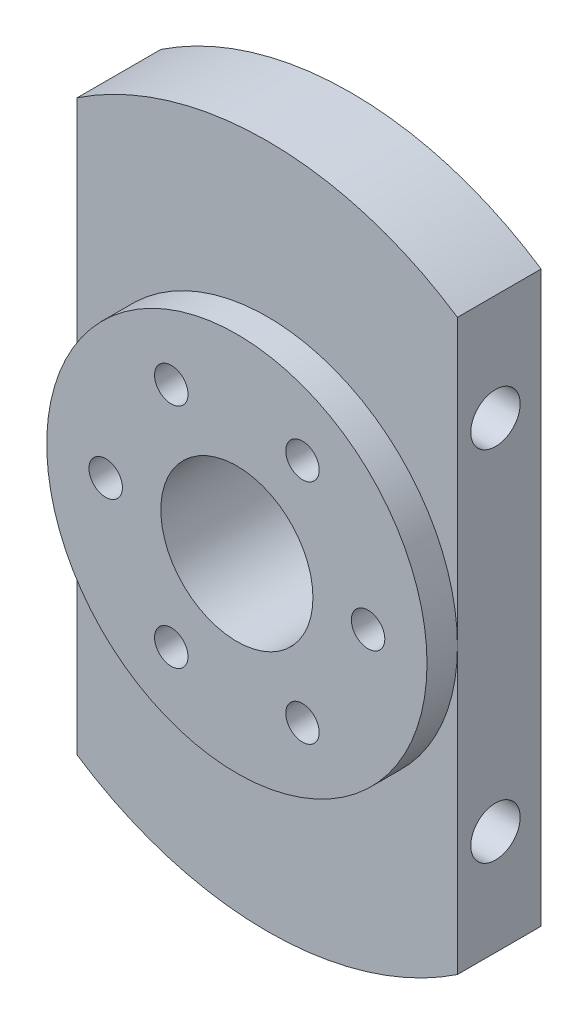
SolidWorks part; units mm, degrees
ref_plane "前视基准面" through (0, 0, 0) normal (0, 0, 1) x (1, 0, 0)
ref_plane "上视基准面" through (0, 0, 0) normal (0, 1, 0) x (1, 0, 0)
ref_plane "右视基准面" through (0, 0, 0) normal (1, 0, 0) x (0, 0, -1)
sketch "草图1" plane through (0, 0, 0) normal (0, 0, 1) x (1, 0, 0)
  circle A0 centre (0, 0) radius 45
  dimension "D1" = 90
extrude "凸台-拉伸1" add sketch "草图1" along normal blind 15
sketch "草图6" plane through (0, 0, 15) normal (0, 0, 1) x (1, 0, 0)
  circle A0 centre (0, 0) radius 10
extrude "切除-拉伸5" cut sketch "草图6" against normal blind 26
sketch "草图7" plane through (0, 0, 15) normal (0, 0, 1) x (1, 0, 0)
  circle A0 centre (17.25, 0) radius 2.2
  circle A1 centre (8.625, -14.9389) radius 2.2
  circle A2 centre (-8.625, -14.9389) radius 2.2
  circle A3 centre (-17.25, 0) radius 2.2
  circle A4 centre (-8.625, 14.9389) radius 2.2
  circle A5 centre (8.625, 14.9389) radius 2.2
  point P15 (0, 0)
  dimension "D1" = 4.4
  dimension "D2" = 17.25
  dimension "D3" = 6
extrude "切除-拉伸6" cut sketch "草图7" against normal through all
sketch "草图8" plane through (0, 0, 15) normal (0, 0, 1) x (1, 0, 0)
  line L0 (-45, 0) -> (45, 0) construction
  line L1 (-25, -37.4166) -> (-25, 37.4166)
  line L2 (0, 45) -> (0, -45) construction
  line L3 (25, -37.4166) -> (25, 37.4166)
  circle A0 centre (17.25, 0) radius 2.2 construction
  circle A1 centre (0, 0) radius 45
  circle A2 centre (0, 0) radius 45
  circle A3 centre (-17.25, 0) radius 2.2 construction
  circle A4 centre (17.25, 0) radius 2.2
  circle A5 centre (-17.25, 0) radius 2.2
  circle M11 centre (0, 0) radius 45
  dimension "D2" = 25
  dimension "D1" = 0
extrude "切除-拉伸7" cut sketch "草图8" against normal through all contours L1 M11 | L3 M11
sketch "草图9" plane through (25, 0, 0) normal (1, 0, 0) x (0, 0, -1)
  line L0 (-15, 0) -> (0, 0) construction
  line L5 (-15, 37.4166) -> (-15, -37.4166)
  line L6 (-15, -37.4166) -> (0, -37.4166)
  line L7 (0, -37.4166) -> (0, 37.4166)
  line L8 (0, 37.4166) -> (-15, 37.4166)
  line L9 (-15, 37.4166) -> (-15, -37.4166)
  line L10 (-15, -37.4166) -> (0, -37.4166)
  line L11 (0, -37.4166) -> (0, 37.4166)
  line L12 (0, 37.4166) -> (-15, 37.4166)
  circle A0 centre (-6, 23.45) radius 3.25
  circle A1 centre (-6, -23.63) radius 3.25
  dimension "D2" = 6.5
  dimension "D3" = 6.5
  dimension "D4" = 6
  dimension "D5" = 47.08
  dimension "D6" = 6
  dimension "D7" = 23.45
  dimension "D1" = 0
extrude "切除-拉伸8" cut sketch "草图9" against normal through all contours A0 | A1
sketch "草图11" plane through (0, 0, 0) normal (0, 0, -1) x (-1, 0, 0)
  circle A0 centre (-8.625, 14.9389) radius 4
  circle A1 centre (0, 0) radius 10
  circle A2 centre (0, 0) radius 10
  circle A3 centre (-8.625, -14.9389) radius 2.2
  circle A4 centre (-8.625, -14.9389) radius 2.2
  circle A5 centre (8.625, -14.9389) radius 2.2
  circle A6 centre (8.625, -14.9389) radius 2.2
  circle A7 centre (17.25, 0) radius 2.2
  circle A8 centre (17.25, 0) radius 2.2
  circle A9 centre (8.625, 14.9389) radius 2.2
  circle A10 centre (8.625, 14.9389) radius 2.2
  circle A11 centre (-8.625, 14.9389) radius 2.2
  circle A12 centre (-8.625, 14.9389) radius 2.2
  circle A13 centre (-17.25, 0) radius 2.2
  circle A14 centre (-17.25, 0) radius 2.2
  circle A15 centre (-17.25, 0) radius 4
  circle A16 centre (-8.625, -14.9389) radius 4
  circle A17 centre (8.625, 14.9389) radius 4
  circle A18 centre (8.625, -14.9389) radius 4
  circle A19 centre (17.25, 0) radius 4
  dimension "D8" = 8
  dimension "D9" = 8
  dimension "D10" = 8
  dimension "D11" = 8
  dimension "D12" = 8
  dimension "D13" = 8
  dimension "D1" = 0
  dimension "D2" = 0
  dimension "D3" = 0
  dimension "D4" = 0
  dimension "D5" = 0
  dimension "D6" = 0
  dimension "D7" = 0
extrude "切除-拉伸9" cut sketch "草图11" against normal blind 9 contours A15 | A0 | A16 | A18 | A19 | A17
sketch "草图12" plane through (25, 0, 0) normal (1, 0, 0) x (0, 0, -1)
  line L0 (0, -37.4166) -> (0, 37.4166) construction
  line L1 (0, -37.4166) -> (0, 37.4166)
  line L2 (0, -37.4166) -> (-15, -37.4166) construction
  line L3 (-15, -37.4166) -> (-15, 37.4166) construction
  line L4 (0, 37.4166) -> (-15, 37.4166) construction
  line L5 (0, -37.4166) -> (-15, -37.4166)
  line L6 (-15, -37.4166) -> (-15, 37.4166)
  line L7 (0, 37.4166) -> (-15, 37.4166)
  circle A1 centre (-6, -23.63) radius 3.25
  circle A2 centre (-6, -23.63) radius 3.25
  circle A3 centre (-6, 23.45) radius 3.25
  circle A4 centre (-6, 23.45) radius 3.25
  dimension "D1" = 0
  dimension "D2" = 0
sketch "草图13" plane through (0, 0, 15) normal (0, 0, 1) x (1, 0, 0)
  line L3 (-25, 37.4166) -> (-25, -37.4166)
  line L4 (25, -37.4166) -> (25, 37.4166)
  line L5 (-25, 37.4166) -> (-25, -37.4166)
  line L6 (25, -37.4166) -> (25, 37.4166)
  circle A0 centre (0, 0) radius 25
  arc A3 (-25, -37.4166) -> (25, -37.4166) centre (0, 0) ccw
  arc A4 (25, 37.4166) -> (-25, 37.4166) centre (0, 0) ccw
  arc A5 (-25, -37.4166) -> (25, -37.4166) centre (0, 0) ccw
  arc A6 (25, 37.4166) -> (-25, 37.4166) centre (0, 0) ccw
  line M6 (-25, 37.4166) -> (-25, -37.4166)
  arc M7 (-25, -37.4166) -> (25, -37.4166) centre (0, 0) ccw
  line M8 (25, -37.4166) -> (25, 37.4166)
  arc M9 (25, 37.4166) -> (-25, 37.4166) centre (0, 0) ccw
  dimension "D1" = 50
  dimension "D2" = 0
extrude "切除-拉伸10" cut sketch "草图13" against normal blind 4 contours A0 L6 M9 M6 | A0 L5 M7 M8
